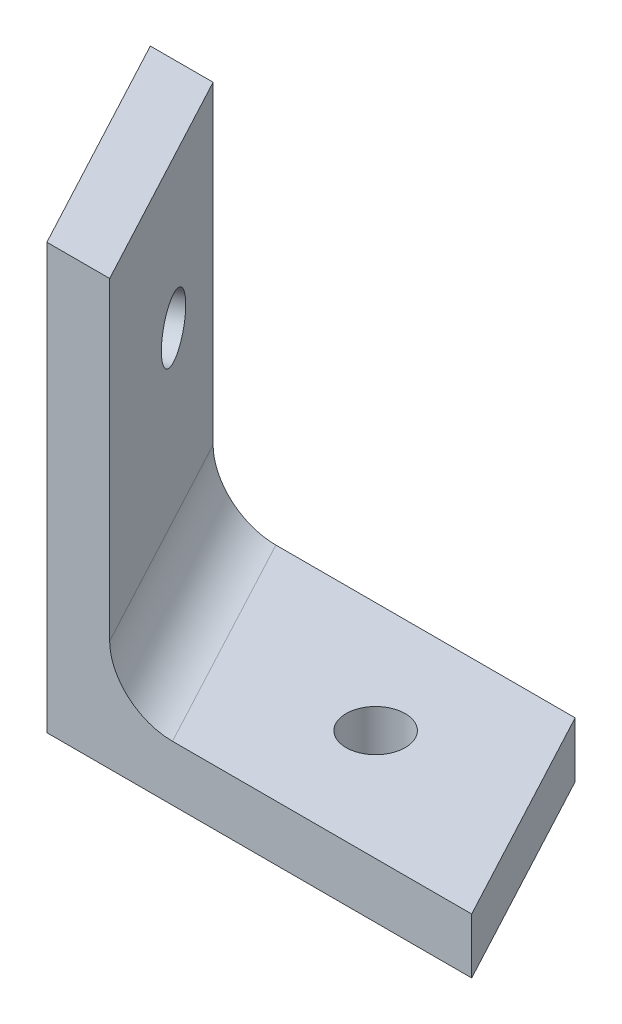
SolidWorks part; units mm, degrees
ref_plane "前视基准面" through (0, 0, 0) normal (0, 0, 1) x (1, 0, 0)
ref_plane "上视基准面" through (0, 0, 0) normal (0, 1, 0) x (1, 0, 0)
ref_plane "右视基准面" through (0, 0, 0) normal (1, 0, 0) x (0, 0, -1)
sketch "草图1" plane through (0, 0, 0) normal (0, 1, 0) x (1, 0, 0)
  line L0 (-80, 15) -> (-72, 0) construction
  line L1 (-72, 0) -> (72, 0) construction
  line L2 (72, 0) -> (80, 15) construction
  line L3 (80, 15) -> (-80, 15) construction
  line L4 (0, 15) -> (0, 0) construction
  line L5 (-80, 15) -> (-57, 15)
  line L6 (-80, 15) -> (-73.6, 3)
  line L7 (-73.6, 3) -> (-50.6, 3)
  line L8 (-50.6, 3) -> (-57, 15)
  dimension "D1" = 144
  dimension "D2" = 160
  dimension "D3" = 15
  dimension "D4" = 12
  dimension "D5" = 23
extrude "凸台-拉伸1" add sketch "草图1" along normal blind 3
sketch "草图2" plane through (0, 3, 0) normal (0, 1, 0) x (1, 0, 0)
  line L0 (-80, 15) -> (-73.6, 3)
  line L1 (-73.6, 3) -> (-70.2, 3)
  line L2 (-73.6, 3) -> (-50.6, 3) construction
  line L3 (-70.2, 3) -> (-76.6, 15)
  line L4 (-57, 15) -> (-80, 15) construction
  line L5 (-76.6, 15) -> (-80, 15)
  dimension "D1" = 3
extrude "凸台-拉伸2" add sketch "草图2" along normal blind 20
sketch "草图3" plane through (0, 0, 0) normal (0, 1, 0) x (1, 0, 0)
  line L1 (-61.8, 9) -> (-76.8, 9) construction
  line L6 (-80, 15) -> (-73.6, 3) construction
  circle A0 centre (-61.8, 9) radius 1.6
  dimension "D1" = 3.2
  dimension "D3" = 15
extrude "切除-拉伸1" cut sketch "草图3" along normal up to next
sketch "草图4" plane through (-56.0554, 0, 29.8962) normal (0.8824, 0, -0.4706) x (-0.4706, 0, -0.8824)
  line L1 (44.0824, 0) -> (44.0824, 15) construction
  line L3 (50.8824, 0) -> (37.2824, 0) construction
  circle A0 centre (44.0824, 15) radius 1.6
  dimension "D1" = 3.2
  dimension "D2" = 15
extrude "切除-拉伸2" cut sketch "草图4" along normal up to next
fillet "圆角1" radius 3 1 edges at (-73.4, 3, -9)
